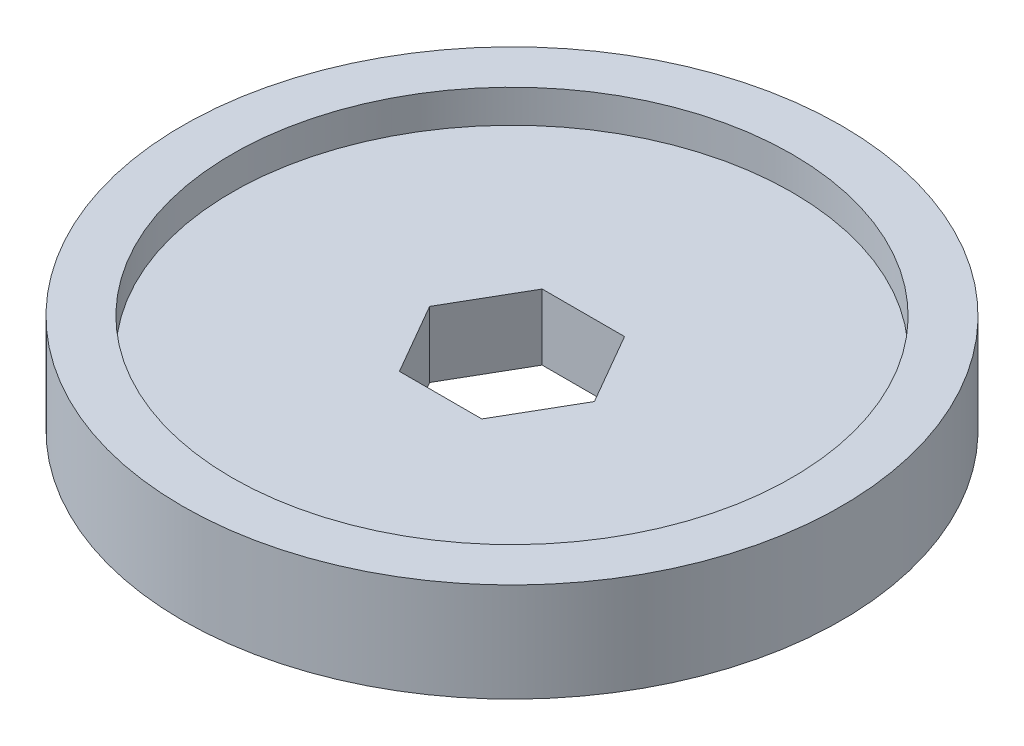
SolidWorks part; units mm, degrees
material "ABS"
ref_plane "Front Plane" through (0, 0, 0) normal (0, 0, 1) x (1, 0, 0)
ref_plane "Top Plane" through (0, 0, 0) normal (0, 1, 0) x (1, 0, 0)
ref_plane "Right Plane" through (0, 0, 0) normal (1, 0, 0) x (0, 0, -1)
sketch "Sketch1" plane through (0, 0, 0) normal (0, 1, 0) x (1, 0, 0)
  line L0 (0, 0) -> (6.35, 0) construction
  line L1 (6.35, 0) -> (3.175, 5.4993)
  line L2 (3.175, 5.4993) -> (-3.175, 5.4993)
  line L3 (-3.175, 5.4993) -> (-6.35, 0)
  line L4 (-6.35, 0) -> (-3.175, -5.4993)
  line L5 (-3.175, -5.4993) -> (3.175, -5.4993)
  line L6 (3.175, -5.4993) -> (6.35, 0)
  circle A0 centre (0, 0) radius 5.4993 construction
  circle A1 centre (0, 0) radius 25.4
  circle A2 centre (0, 0) radius 27.6225 construction
  dimension "D2" = 2.2225
  dimension "D3" = 55.245
  dimension "D1" = 12.7
extrude "Boss-Extrude1" add sketch "Sketch1" along normal blind 5.08
sketch "Sketch2" plane through (0, 5.08, 0) normal (0, 1, 0) x (1, 0, 0)
  circle A0 centre (0, 0) radius 25.4
  circle A1 centre (0, 0) radius 21.59
  circle A2 centre (0, 0) radius 25.4 construction
  dimension "D1" = 3.81
extrude "Boss-Extrude2" add sketch "Sketch2" along normal blind 2.54
